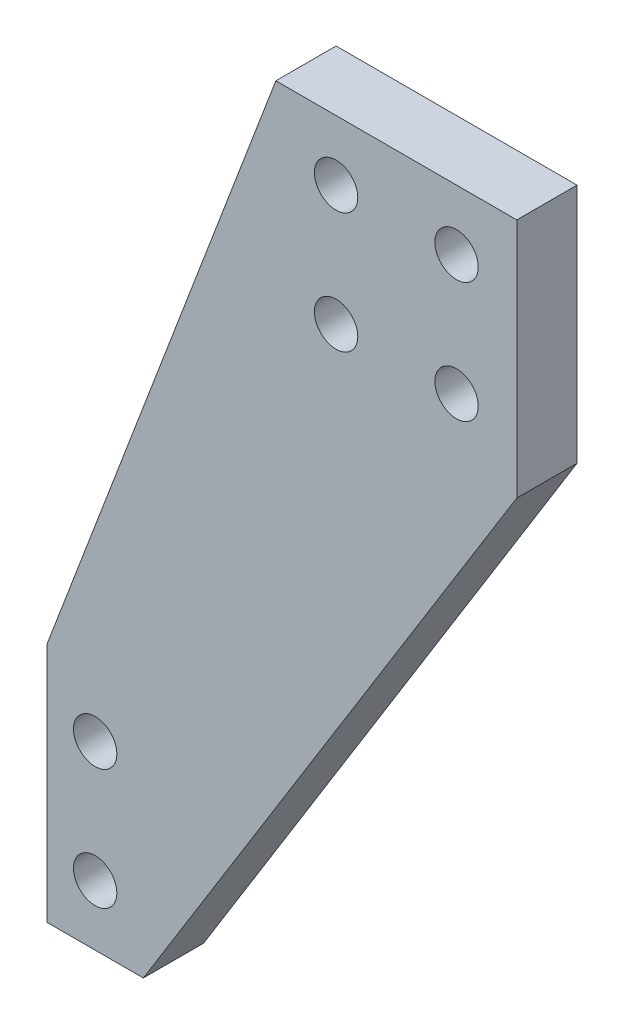
SolidWorks part; units mm, degrees
ref_plane "Front Plane" through (0, 0, 0) normal (0, 0, 1) x (1, 0, 0)
ref_plane "Top Plane" through (0, 0, 0) normal (0, 1, 0) x (1, 0, 0)
ref_plane "Right Plane" through (0, 0, 0) normal (1, 0, 0) x (0, 0, -1)
sketch "Sketch1" plane through (0, 0, 0) normal (0, 0, 1) x (1, 0, 0)
  line L0 (0, 0) -> (24.13, 63.5)
  line L1 (24.13, 63.5) -> (49.53, 63.5)
  line L2 (49.53, 63.5) -> (49.53, 38.1)
  line L3 (49.53, 38.1) -> (10.16, -25.4)
  line L4 (10.16, -25.4) -> (0, -25.4)
  line L5 (0, -25.4) -> (0, 0)
  circle A0 centre (5.08, -19.05) radius 2.286
  circle A1 centre (5.08, -6.35) radius 2.286
  circle A2 centre (43.18, 57.15) radius 2.286
  circle A3 centre (30.48, 57.15) radius 2.286
  circle A4 centre (30.48, 44.45) radius 2.286
  circle A5 centre (43.18, 44.45) radius 2.286
  dimension "D14" = 4.572
  dimension "D1" = 5.08
  dimension "D2" = 10.16
  dimension "D3" = 25.4
  dimension "D4" = 6.35
  dimension "D5" = 12.7
  dimension "D6" = 6.35
  dimension "D7" = 6.35
  dimension "D8" = 25.4
  dimension "D9" = 25.4
  dimension "D12" = 49.53
  dimension "D13" = 88.9
  dimension "D10" = 2
  dimension "D11" = 2
extrude "Boss-Extrude1" add sketch "Sketch1" along normal blind 6.35
